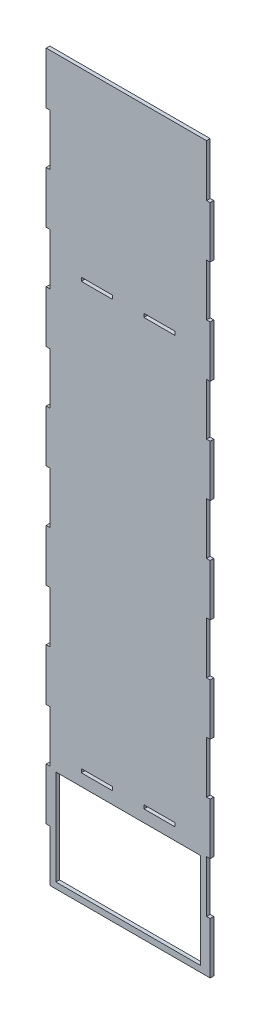
SolidWorks part; units mm, degrees
ref_plane "Front Plane" through (0, 0, 0) normal (0, 0, 1) x (1, 0, 0)
ref_plane "Top Plane" through (0, 0, 0) normal (0, 1, 0) x (1, 0, 0)
ref_plane "Right Plane" through (0, 0, 0) normal (1, 0, 0) x (0, 0, -1)
sketch "Sketch1" plane through (0, 0, 0) normal (0, 0, 1) x (1, 0, 0)
  line L0 (-68, 0) -> (65, 0)
  line L1 (65, 0) -> (65, -43.0071)
  line L2 (65, -43.0071) -> (68, -43.0071)
  line L3 (68, -43.0071) -> (68, -85.7143)
  line L4 (68, -85.7143) -> (65, -85.7143)
  line L5 (65, -85.7143) -> (65, -128.7214)
  line L6 (65, -128.7214) -> (68, -128.7214)
  line L7 (68, -128.7214) -> (68, -171.4286)
  line L8 (68, -171.4286) -> (65, -171.4286)
  line L9 (65, -171.4286) -> (65, -214.4357)
  line L10 (65, -214.4357) -> (68, -214.4357)
  line L11 (68, -214.4357) -> (68, -257.1429)
  line L12 (68, -257.1429) -> (65, -257.1429)
  line L13 (65, -257.1429) -> (65, -300.15)
  line L14 (65, -300.15) -> (68, -300.15)
  line L15 (68, -300.15) -> (68, -342.8571)
  line L16 (68, -342.8571) -> (65, -342.8571)
  line L17 (65, -342.8571) -> (65, -385.8643)
  line L18 (65, -385.8643) -> (68, -385.8643)
  line L19 (68, -385.8643) -> (68, -428.5714)
  line L20 (68, -428.5714) -> (65, -428.5714)
  line L21 (65, -428.5714) -> (65, -471.5786)
  line L22 (65, -471.5786) -> (68, -471.5786)
  line L23 (68, -471.5786) -> (68, -514.2857)
  line L24 (68, -514.2857) -> (65, -514.2857)
  line L25 (65, -514.2857) -> (65, -557.2929)
  line L26 (65, -557.2929) -> (68, -557.2929)
  line L27 (68, -557.2929) -> (68, -600)
  line L28 (68, -600) -> (-65, -600)
  line L30 (-68, -514.2857) -> (-65, -514.2857)
  line L31 (-65, -514.2857) -> (-65, -471.5786)
  line L32 (-65, -471.5786) -> (-68, -471.5786)
  line L33 (-68, -471.5786) -> (-68, -428.5714)
  line L34 (-68, -428.5714) -> (-65, -428.5714)
  line L35 (-65, -428.5714) -> (-65, -385.8643)
  line L36 (-65, -385.8643) -> (-68, -385.8643)
  line L37 (-68, -385.8643) -> (-68, -342.8571)
  line L38 (-68, -342.8571) -> (-65, -342.8571)
  line L39 (-65, -342.8571) -> (-65, -300.15)
  line L40 (-65, -300.15) -> (-68, -300.15)
  line L41 (-68, -300.15) -> (-68, -257.1429)
  line L42 (-68, -257.1429) -> (-65, -257.1429)
  line L43 (-65, -257.1429) -> (-65, -214.4357)
  line L44 (-65, -214.4357) -> (-68, -214.4357)
  line L45 (-68, -214.4357) -> (-68, -171.4286)
  line L46 (-68, -171.4286) -> (-65, -171.4286)
  line L47 (-65, -171.4286) -> (-65, -128.7214)
  line L48 (-65, -128.7214) -> (-68, -128.7214)
  line L49 (-68, -128.7214) -> (-68, -85.7143)
  line L50 (-68, -85.7143) -> (-65, -85.7143)
  line L51 (-65, -85.7143) -> (-65, -43.0071)
  line L52 (-65, -43.0071) -> (-68, -43.0071)
  line L53 (-68, -43.0071) -> (-68, 0)
  line L56 (-65, -43.0071) -> (-65, -0.3) construction
  line L57 (-65, -0.3) -> (-65, 0) construction
  line L58 (-38.88, -151.5) -> (-65, -151.5) construction
  line L59 (-60, -595) -> (60, -595)
  line L60 (-60, -595) -> (-60, -516)
  line L61 (-60, -516) -> (60, -516)
  line L62 (60, -595) -> (60, -516)
  line L63 (-60, -595) -> (60, -516) construction
  line L64 (-60, -516) -> (60, -595) construction
  line L65 (-38.88, -153) -> (-13.06, -153)
  line L66 (-38.88, -153) -> (-38.88, -150)
  line L67 (-38.88, -150) -> (-13.06, -150)
  line L68 (-13.06, -153) -> (-13.06, -150)
  line L69 (-38.88, -153) -> (-13.06, -150) construction
  line L70 (-38.88, -150) -> (-13.06, -153) construction
  line L71 (13.06, -153) -> (38.88, -153)
  line L72 (13.06, -153) -> (13.06, -150)
  line L73 (13.06, -150) -> (38.88, -150)
  line L74 (38.88, -153) -> (38.88, -150)
  line L75 (13.06, -153) -> (38.88, -150) construction
  line L76 (13.06, -150) -> (38.88, -153) construction
  line L77 (-13.06, -151.5) -> (13.06, -151.5) construction
  line L78 (38.88, -151.5) -> (65, -151.5) construction
  line L79 (-13.06, -150) -> (12.76, -150) construction
  line L80 (12.76, -150) -> (13.06, -150) construction
  line L81 (-38.88, -506) -> (-38.88, -503)
  line L82 (-38.88, -506) -> (-13.06, -506)
  line L83 (-13.06, -506) -> (-13.06, -503)
  line L84 (-38.88, -503) -> (-13.06, -503)
  line L85 (13.06, -506) -> (13.06, -503)
  line L86 (13.06, -506) -> (38.88, -506)
  line L87 (38.88, -506) -> (38.88, -503)
  line L88 (13.06, -503) -> (38.88, -503)
  line L89 (-68, -514.2857) -> (-68, -557.2929)
  line L90 (-68, -557.2929) -> (-65, -557.2929)
  line L91 (-65, -557.2929) -> (-65, -600)
  point P0 (0, -555.5)
  point P62 (25.97, -151.5)
  point P63 (0, -151.5)
  point P64 (-25.97, -151.5)
  dimension "D1" = 0.3
  dimension "D2" = 600
  dimension "D3" = 130
  dimension "D4" = 5
  dimension "D5" = 3
  dimension "D6" = 3
  dimension "D7" = 0.3
  dimension "D9" = 150
  dimension "D10" = 350
  dimension "D11" = 10
  dimension "D12" = 5
  dimension "D8" = 2
extrude "Boss-Extrude1" add sketch "Sketch1" along normal blind 3
